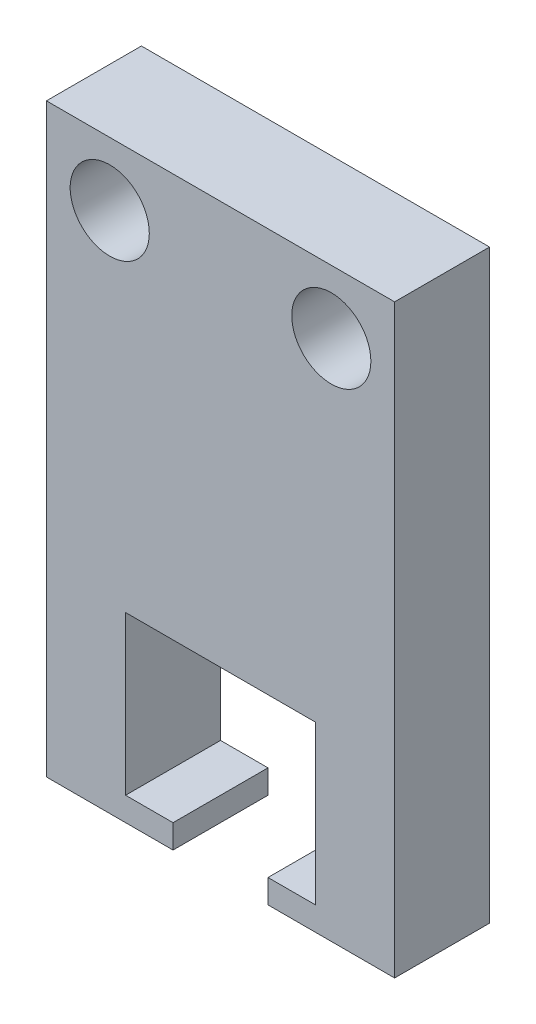
SolidWorks part; units mm, degrees
material "Brass"
ref_plane "Front Plane" through (0, 0, 0) normal (0, 0, 1) x (1, 0, 0)
ref_plane "Top Plane" through (0, 0, 0) normal (0, 1, 0) x (1, 0, 0)
ref_plane "Right Plane" through (0, 0, 0) normal (1, 0, 0) x (0, 0, -1)
sketch "Sketch1" plane through (0, 0, 0) normal (0, 0, 1) x (1, 0, 0)
  line L0 (0, 18.5) -> (0, -18.5) construction
  line L1 (-11, 18.5) -> (11, 18.5)
  line L2 (-11, 18.5) -> (-11, -18.5)
  line L3 (-11, -18.5) -> (11, -18.5)
  line L4 (11, 18.5) -> (11, -18.5)
  line L5 (-7, 12) -> (7, 12) construction
  line L6 (0, 12) -> (0, -7.8801) construction
  line L8 (6, -7) -> (-6, -7)
  line L9 (6, -7) -> (6, -17)
  line L10 (6, -17) -> (-6, -17)
  line L11 (-6, -7) -> (-6, -17)
  line L12 (-3, -17) -> (3, -17)
  line L13 (-3, -17) -> (-3, -18.5)
  line L14 (-3, -18.5) -> (3, -18.5)
  line L15 (3, -17) -> (3, -18.5)
  circle A0 centre (-7, 14.5) radius 2.5
  circle A1 centre (7, 14.5) radius 2.5
  point P23 (-3, -17.75)
  dimension "D1" = 5
  dimension "D2" = 5
  dimension "D7" = 4
  dimension "D3" = 37
  dimension "D4" = 22
  dimension "D5" = 14
  dimension "D6" = 7
  dimension "D8" = 19
  dimension "D9" = 12
  dimension "D10" = 10
  dimension "D11" = 3
  dimension "D12" = 3
  dimension "D13" = 6
extrude "Boss-Extrude2" add sketch "Sketch1" along normal blind 6 contours L15 L10 L13 L3 | A0 | A1
sketch "Sketch3" plane through (0, 0, 0) normal (0, 0, -1) x (-1, 0, 0)
  line L0 (-6, -17) -> (6, -17) construction
  line L1 (0, -17) -> (-3, -17)
  line L3 (0, -18.5) -> (-3, -18.5)
  line L4 (-3, -17) -> (-3, -18.5)
  line L5 (11, -18.5) -> (-11, -18.5) construction
  line L7 (0, -17) -> (3, -17)
  line L9 (0, -18.5) -> (3, -18.5)
  line L10 (3, -17) -> (3, -18.5)
extrude "Cut-Extrude2" cut sketch "Sketch3" against normal blind 6
